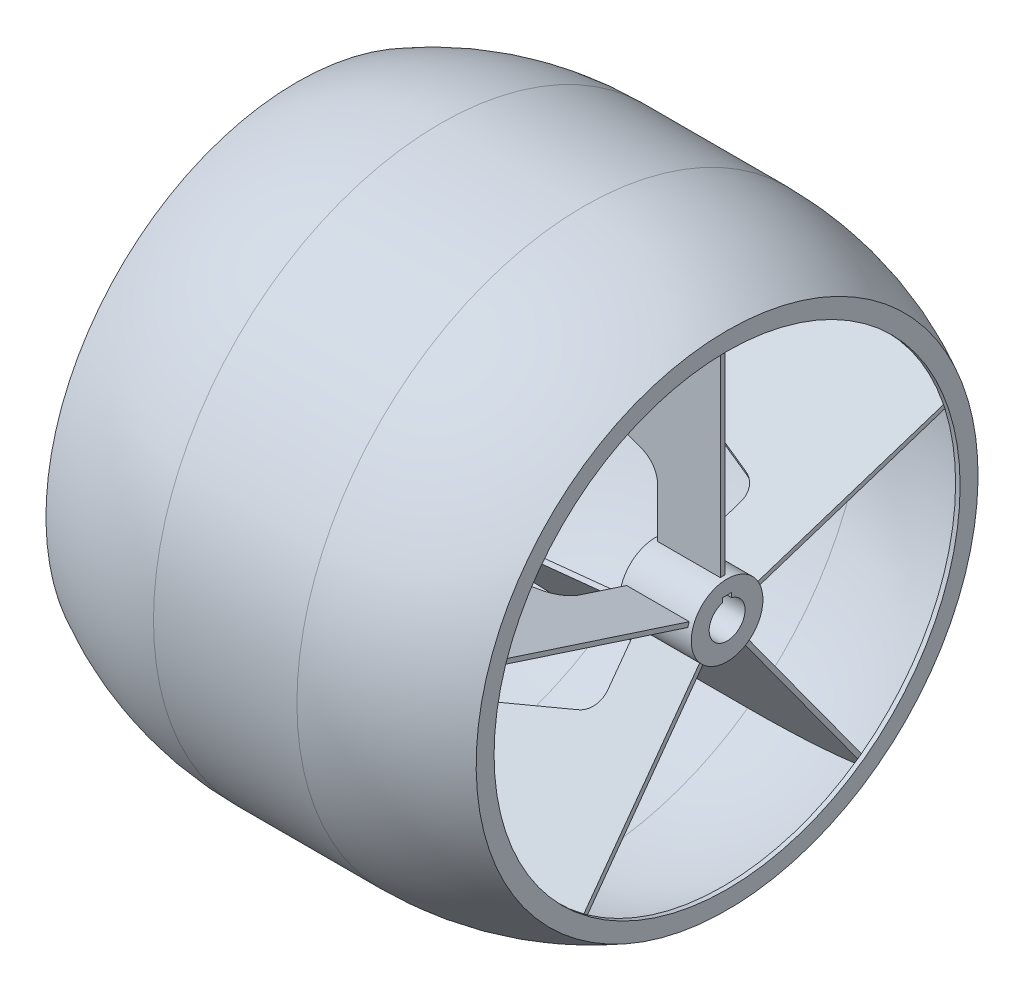
SolidWorks part; units mm, degrees
material "Thornel Mat VMA"
ref_plane "Front Plane" through (0, 0, 0) normal (0, 0, 1) x (1, 0, 0)
ref_plane "Top Plane" through (0, 0, 0) normal (0, 1, 0) x (1, 0, 0)
ref_plane "Right Plane" through (0, 0, 0) normal (1, 0, 0) x (0, 0, -1)
sketch "Sketch1" plane through (0, 0, 0) normal (0, 0, 1) x (1, 0, 0)
  line L0 (76.2, 0) -> (0, 0) construction
  line L1 (0, 0) -> (0, 101.6) construction
  line L2 (0, 101.6) -> (25.4, 101.6)
  line L3 (76.2, 88.9) -> (76.2, 82.55)
  line L4 (0, 99.9998) -> (25.4, 99.9998)
  line L5 (74.5998, 87.935) -> (74.5998, 82.55)
  line L6 (74.5998, 82.55) -> (76.2, 82.55)
  line L7 (-74.5998, 82.55) -> (-76.2, 82.55)
  line L8 (-76.2, 88.9) -> (-76.2, 82.55)
  line L9 (-74.5998, 87.935) -> (-74.5998, 82.55)
  line L10 (0, 101.6) -> (-25.4, 101.6)
  line L11 (0, 99.9998) -> (-25.4, 99.9998)
  arc A0 (25.4, 101.6) -> (76.2, 88.9) centre (25.4, -6.35) cw
  arc A1 (25.4, 99.9998) -> (74.5998, 87.935) centre (25.4, -6.35) cw
  arc A2 (-25.4, 101.6) -> (-76.2, 88.9) centre (-25.4, -6.35) ccw
  arc A3 (-25.4, 99.9998) -> (-74.5998, 87.935) centre (-25.4, -6.35) ccw
  dimension "D1" = 203.2
  dimension "D2" = 152.4
  dimension "D3" = 50.8
  dimension "D4" = 12.7
  dimension "D5" = 6.35
  dimension "D6" = 1.6002
revolve "Revolve1" add sketch "Sketch1" angle 360 about L0
sketch "Sketch2" plane through (0, 0, 0) normal (1, 0, 0) x (0, 0, -1)
  line L0 (-1.5875, 6.1484) -> (-1.5875, 7.7359)
  line L1 (-1.5875, 7.7359) -> (1.5875, 7.7359)
  line L2 (1.5875, 7.7359) -> (1.5875, 6.1484)
  line L3 (0, 0) -> (0, 7.7359) construction
  arc A0 (-1.5875, 6.1484) -> (1.5875, 6.1484) centre (0, 0) ccw
  circle A1 centre (0, 0) radius 12.7
  dimension "D1" = 6.35
  dimension "D4" = 25.4
  dimension "D2" = 3.175
  dimension "D3" = 1.5875
extrude "Boss-Extrude1" add sketch "Sketch2" along normal blind 25.4 from offset 50.8 separate body
sketch "Sketch3" plane through (0, 0, 0) normal (0, 0, 1) x (1, 0, 0)
  line L0 (74.5998, 87.935) -> (74.5998, 9.525)
  line L3 (-74.5998, -82.55) -> (-74.5998, 82.55) construction
  line L5 (-25.4, 99.9998) -> (25.4, 99.9998)
  line L6 (25.4, 101.6) -> (25.4, -101.6) construction
  line L7 (-25.4, 101.6) -> (-25.4, -101.6) construction
  line L8 (-74.5998, 87.935) -> (-74.5998, 82.55)
  line L9 (74.5998, 9.525) -> (52.4002, 9.525)
  line L10 (50.8, 12.7) -> (50.8, -12.7) construction
  line L11 (52.4002, 9.525) -> (52.4002, 30.1625)
  line L12 (0, 0) -> (76.2, 0) construction
  line L13 (76.2, -6.35) -> (76.2, 6.1484) construction
  line L14 (46.6086, 38.4337) -> (-74.5998, 82.55)
  arc A0 (25.4, 99.9998) -> (74.5998, 87.935) centre (25.4, -6.35) cw
  arc A1 (-25.4, 99.9998) -> (-74.5998, 87.935) centre (-25.4, -6.35) ccw
  arc A2 (52.4002, 30.1625) -> (46.6086, 38.4337) centre (43.5981, 30.1625) ccw
  dimension "D1" = 60.325
  dimension "D2" = 19.05
  dimension "D3" = 110
  dimension "D4" = 1.6002
extrude "Boss-Extrude2" add sketch "Sketch3" along normal mid plane 1.6002
pattern_circular "CirPattern1" count 5 over 360 about axis through (0, 0, 0) along (1, 0, 0) of "Boss-Extrude2"
